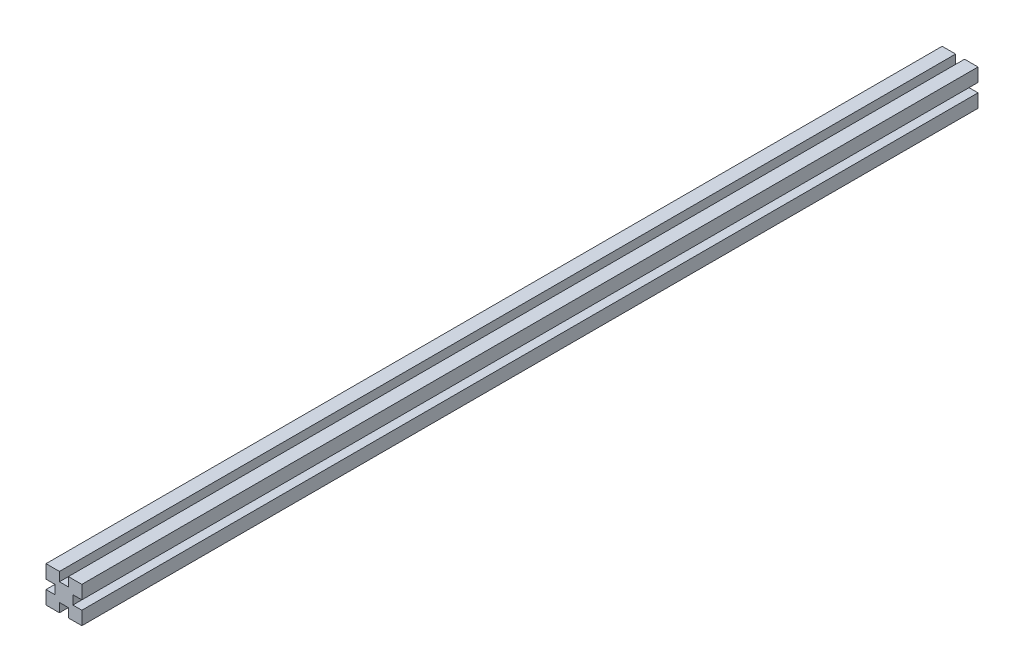
SolidWorks part; units mm, degrees
ref_plane "前视基准面" through (0, 0, 0) normal (0, 0, 1) x (1, 0, 0)
ref_plane "上视基准面" through (0, 0, 0) normal (0, 1, 0) x (1, 0, 0)
ref_plane "右视基准面" through (0, 0, 0) normal (1, 0, 0) x (0, 0, -1)
sketch "草图1" plane through (0, 0, 0) normal (0, 0, 1) x (1, 0, 0)
  line L0 (2.5, 10) -> (2.5, 5)
  line L1 (-10, -10) -> (-2.5, -10)
  line L2 (-10, -10) -> (-10, -2.5)
  line L3 (-10, 10) -> (-2.5, 10)
  line L4 (10, -10) -> (10, -2.5)
  line L5 (-10, -10) -> (10, 10) construction
  line L6 (-10, 10) -> (10, -10) construction
  line L7 (2.5, 5) -> (-2.5, 5)
  line L8 (-2.5, 5) -> (-2.5, 10)
  line L9 (10, -2.5) -> (5, -2.5)
  line L10 (5, -2.5) -> (5, 2.5)
  line L11 (5, 2.5) -> (10, 2.5)
  line L12 (-2.5, -10) -> (-2.5, -5)
  line L13 (-2.5, -5) -> (2.5, -5)
  line L14 (2.5, -5) -> (2.5, -10)
  line L15 (-10, 2.5) -> (-5, 2.5)
  line L16 (-5, 2.5) -> (-5, -2.5)
  line L17 (-5, -2.5) -> (-10, -2.5)
  line L18 (2.5, 10) -> (10, 10)
  line L19 (10, 2.5) -> (10, 10)
  line L20 (2.5, -10) -> (10, -10)
  line L21 (-10, 2.5) -> (-10, 10)
  point P0 (0, 0)
  point P25 (0, 0)
  dimension "D1" = 20
  dimension "D3" = 5
  dimension "D4" = 5
  dimension "D5" = 7.5
  dimension "D6" = 4
extrude "凸台-拉伸1" add sketch "草图1" along normal blind 500
